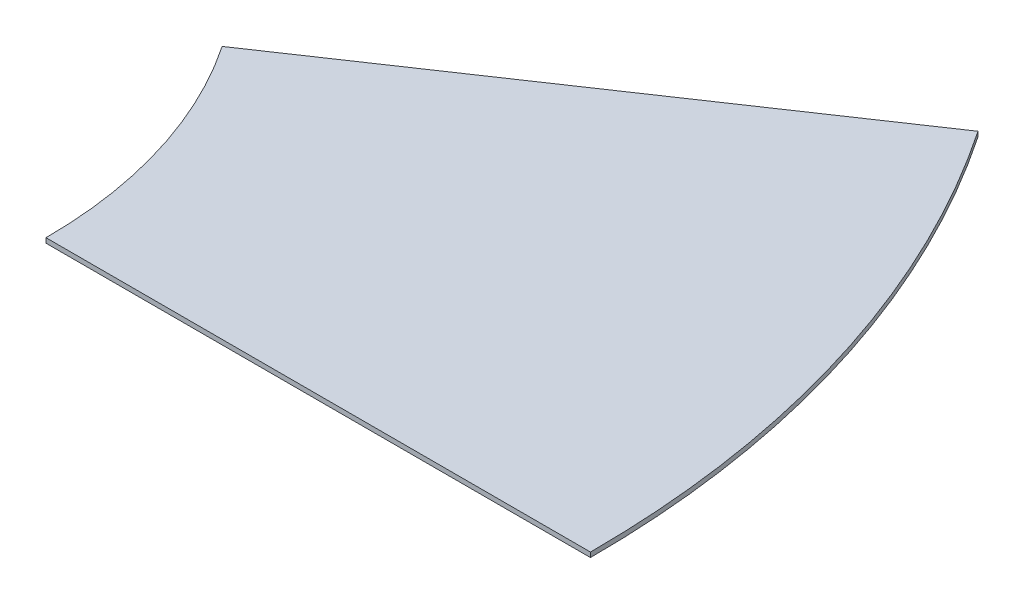
SolidWorks part; units mm, degrees
ref_plane "Front" through (0, 0, 0) normal (0, 0, 1) x (1, 0, 0)
ref_plane "Top" through (0, 0, 0) normal (0, 1, 0) x (1, 0, 0)
ref_plane "Right" through (0, 0, 0) normal (1, 0, 0) x (0, 0, -1)
sketch "草图1" plane through (0, 0, 0) normal (0, 1, 0) x (1, 0, 0)
  line L0 (0, 0) -> (110, 0) construction
  line L1 (91.1941, 61.5112) -> (0, 0) construction
  line L2 (91.1941, 61.5112) -> (41.4519, 27.9596)
  line L3 (110, 0) -> (50, 0)
  arc A0 (110, 0) -> (91.1941, 61.5112) centre (0, 0) ccw
  arc A1 (50, 0) -> (41.4519, 27.9596) centre (0, 0) ccw
  dimension "D2" = 50
  dimension "D3" = 110
  dimension "D1" = 34
extrude "凸台-拉伸1" add sketch "草图1" along normal blind 0.53 contours L3 A1 L2 A0
